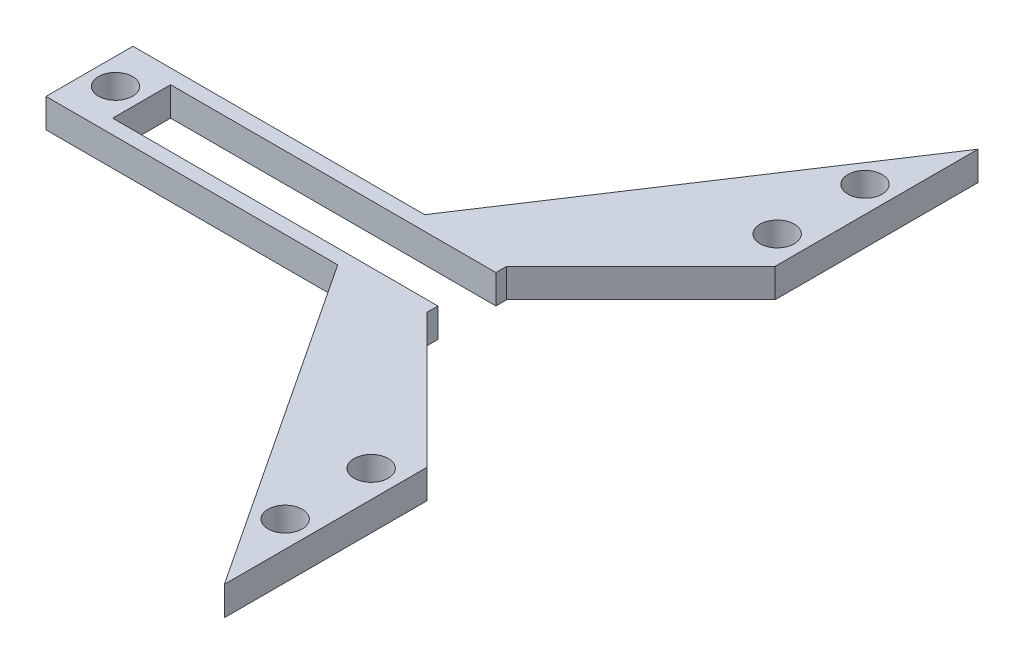
SolidWorks part; units mm, degrees
ref_plane "Front Plane" through (0, 0, 0) normal (0, 0, 1) x (1, 0, 0)
ref_plane "Top Plane" through (0, 0, 0) normal (0, 1, 0) x (1, 0, 0)
ref_plane "Right Plane" through (0, 0, 0) normal (1, 0, 0) x (0, 0, -1)
sketch "Sketch1" plane through (0, 0, 0) normal (0, 1, 0) x (1, 0, 0)
  line L0 (3.2219, 6.0298) -> (14.9883, 17.7962)
  line L1 (0, 0) -> (-25.2984, 0)
  line L3 (0, 5.08) -> (-25.2984, 5.08)
  line L4 (-25.2984, 0) -> (-25.2984, 5.08)
  line L9 (-4.2958, -1.27) -> (-29.8704, -1.27)
  line L10 (3.2219, -0.9498) -> (3.2219, 6.0298)
  line L11 (-4.2958, 6.35) -> (-29.8704, 6.35)
  line L12 (-29.8704, -1.27) -> (-29.8704, 6.35)
  line L13 (3.2219, -0.9498) -> (-29.8704, 6.35) construction
  line L14 (3.1479, 6.0134) -> (-29.8704, -1.27) construction
  line L15 (-55, 0) -> (55, 0) construction
  line L16 (-4.2958, 6.35) -> (14.9883, 35.5762)
  line L17 (14.9883, 35.5762) -> (14.9883, 17.7962)
  line L18 (-5.3349, 2.54) -> (11.7786, 2.54) construction
  line L19 (3.2219, -0.9498) -> (14.9883, -12.7162)
  line L20 (14.9883, -30.4962) -> (14.9883, -12.7162)
  line L21 (-4.2958, -1.27) -> (14.9883, -30.4962)
  line L22 (0, 5.08) -> (3.2219, 5.08)
  line L23 (0, 0) -> (3.2219, 0)
  circle A0 centre (-27.5844, 2.54) radius 1.4986
  circle A1 centre (12.9563, 29.2262) radius 1.4986
  circle A2 centre (12.9563, 23.6382) radius 1.4986
  circle A3 centre (12.9563, -18.5582) radius 1.4986
  circle A4 centre (12.9563, -24.1462) radius 1.4986
  point P6 (-12.5984, 2.54)
  point P19 (3.2219, 2.54)
  dimension "D11" = 2.9972
  dimension "D16" = 2.9972
  dimension "D1" = 25.2984
  dimension "D2" = 5.08
  dimension "D3" = 7.62
  dimension "D4" = 1.27
  dimension "D5" = 33.02
  dimension "D6" = 4.572
  dimension "D7" = 45
  dimension "D8" = 17.78
  dimension "D9" = 19.2841
  dimension "D10" = 25.5746
  dimension "D12" = 2.286
  dimension "D13" = 3.81
  dimension "D14" = 6.9795
  dimension "D15" = 16.6402
  dimension "D17" = 6.35
  dimension "D18" = 2.032
  dimension "D19" = 2.032
  dimension "D20" = 5.588
extrude "Boss-Extrude2" add sketch "Sketch1" along normal blind 2.54 contours L20 L19 L10 L0 L17 L16 L11 L12 L9 L21
sketch "Sketch7" plane through (0, 2.54, 0) normal (0, 1, 0) x (1, 0, 0)
  line L0 (-29.8704, -1.27) -> (-29.8704, 6.35) construction
  line L1 (-4.2958, 6.35) -> (-29.8704, 6.35) construction
  line L2 (14.9883, 35.5762) -> (14.9883, 17.7962) construction
  line L3 (-2.3486, 2.54) -> (7.8486, 2.54) construction
  line L5 (0.1016, 5.08) -> (-25.2984, 5.08)
  line L6 (0.1016, 5.08) -> (0.1016, 0)
  line L7 (0.1016, 0) -> (-25.2984, 0)
  line L8 (-25.2984, 5.08) -> (-25.2984, 0)
  line L9 (0.1016, 5.08) -> (-25.2984, 0) construction
  line L10 (0.1016, 0) -> (-25.2984, 5.08) construction
  line L11 (-4.2958, -1.27) -> (-29.8704, -1.27) construction
  circle A0 centre (-27.5844, 2.54) radius 1.4986
  circle A1 centre (12.7023, 27.9562) radius 1.4986
  circle A2 centre (12.622, 20.3366) radius 1.4986
  circle A3 centre (12.622, -15.2566) radius 1.4986
  circle A4 centre (12.7023, -22.8762) radius 1.4986
  point P19 (-12.5984, 2.54)
  dimension "D1" = 2.9972
  dimension "D6" = 2.9972
  dimension "D8" = 2.3662
  dimension "D2" = 2.286
  dimension "D3" = 3.81
  dimension "D4" = 2.286
  dimension "D5" = 7.62
  dimension "D7" = 7.62
  dimension "D9" = 4.572
  dimension "D10" = 25.4
  dimension "D11" = 1.27
  dimension "D12" = 5.08
extrude "Cut-Extrude1" cut sketch "Sketch7" against normal blind 2.54
sketch "Sketch8" plane through (0, 2.54, 0) normal (0, 1, 0) x (1, 0, 0)
  line L0 (0.1016, 5.08) -> (3.2219, 5.08)
  line L1 (0.1016, 5.08) -> (-25.2984, 5.08) construction
  line L2 (0.1016, 0) -> (0.1016, 5.08) construction
  line L3 (3.2219, -0.9498) -> (3.2219, 6.0298) construction
  line L4 (3.2219, 5.08) -> (3.2219, 0)
  line L5 (-1.397, 0) -> (1.397, 0) construction
  line L6 (3.2219, 0) -> (0, 0)
  line L7 (0, 0) -> (0.1016, 5.08)
extrude "Cut-Extrude2" cut sketch "Sketch8" against normal through all
